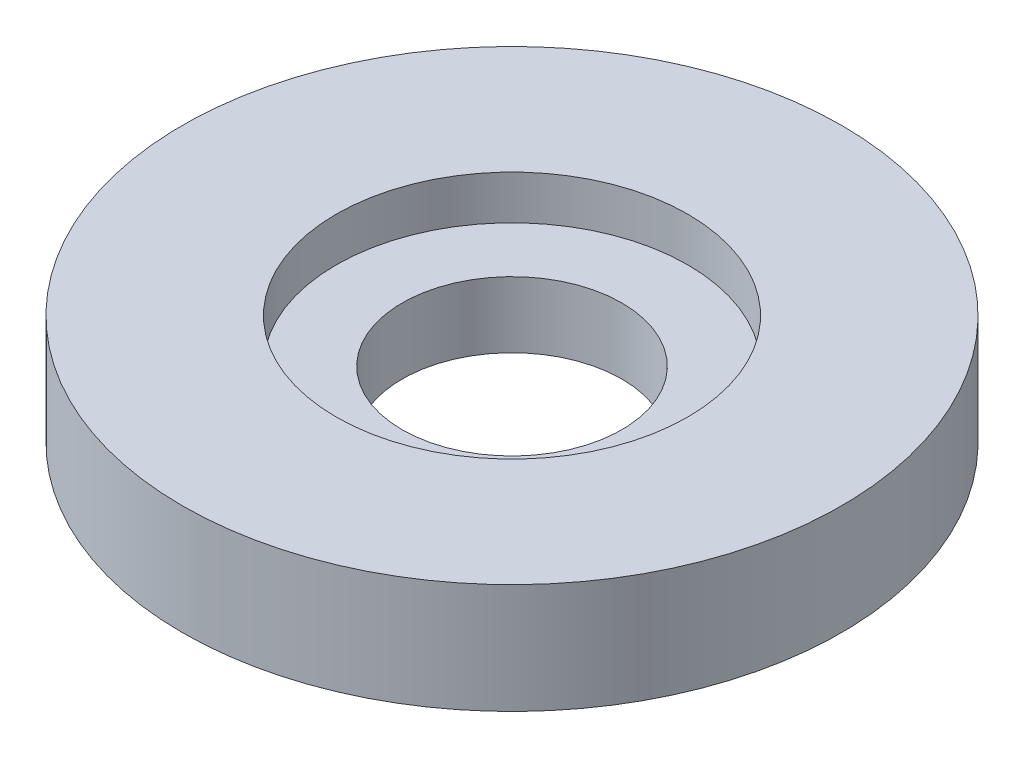
SolidWorks part; units mm, degrees
ref_plane "Front Plane" through (0, 0, 0) normal (0, 0, 1) x (1, 0, 0)
ref_plane "Top Plane" through (0, 0, 0) normal (0, 1, 0) x (1, 0, 0)
ref_plane "Right Plane" through (0, 0, 0) normal (1, 0, 0) x (0, 0, -1)
sketch "Sketch1" plane through (0, 0, 0) normal (0, 1, 0) x (1, 0, 0)
  circle A0 centre (0, 0) radius 15
  circle A1 centre (0, 0) radius 5
  dimension "D1" = 30
  dimension "D2" = 10
extrude "Boss-Extrude1" add sketch "Sketch1" along normal blind 5
sketch "Sketch2" plane through (0, 5, 0) normal (0, 1, 0) x (1, 0, 0)
  circle A0 centre (0, 0) radius 8
  dimension "D1" = 16
extrude "Cut-Extrude1" cut sketch "Sketch2" against normal blind 2
